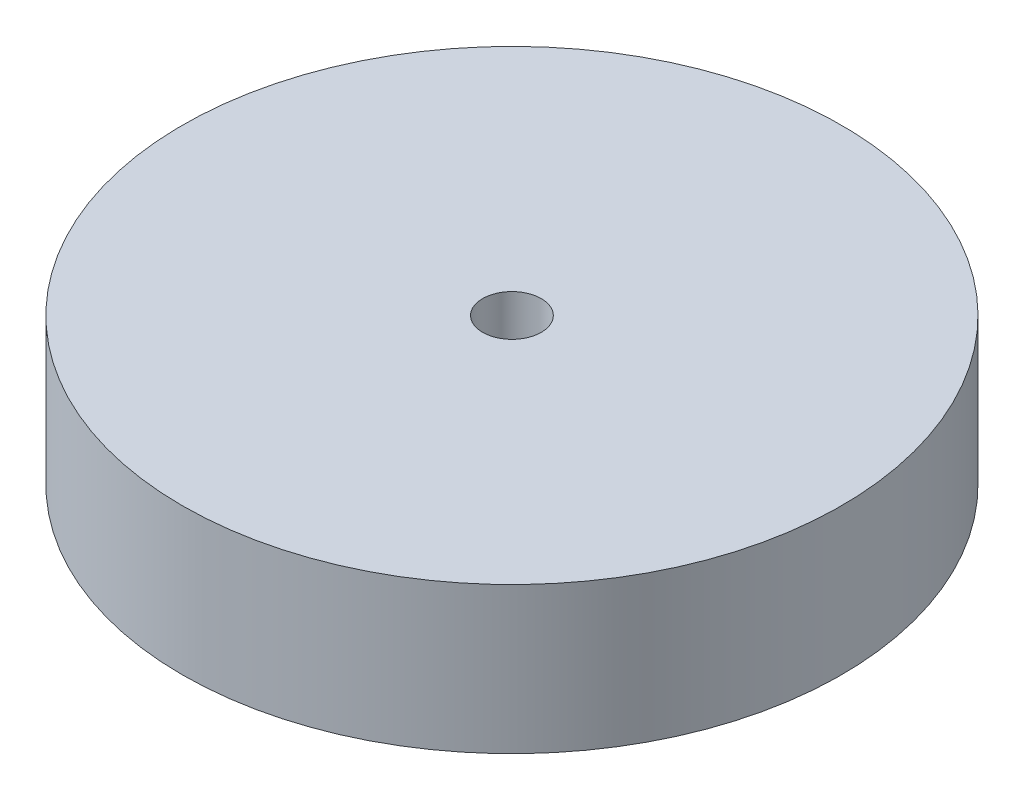
SolidWorks part; units mm, degrees
ref_plane "Front Plane" through (0, 0, 0) normal (0, 0, 1) x (1, 0, 0)
ref_plane "Top Plane" through (0, 0, 0) normal (0, 1, 0) x (1, 0, 0)
ref_plane "Right Plane" through (0, 0, 0) normal (1, 0, 0) x (0, 0, -1)
sketch "Sketch1" plane through (0, 0, 0) normal (0, 1, 0) x (1, 0, 0)
  circle A0 centre (0, 0) radius 45
  dimension "D1" = 90
extrude "Boss-Extrude1" add sketch "Sketch1" along normal blind 20 contours A0
sketch "Sketch2" plane through (0, 20, 0) normal (0, 1, 0) x (1, 0, 0)
  circle A0 centre (0, 0) radius 4
extrude "Cut-Extrude1" cut sketch "Sketch2" against normal up to next
